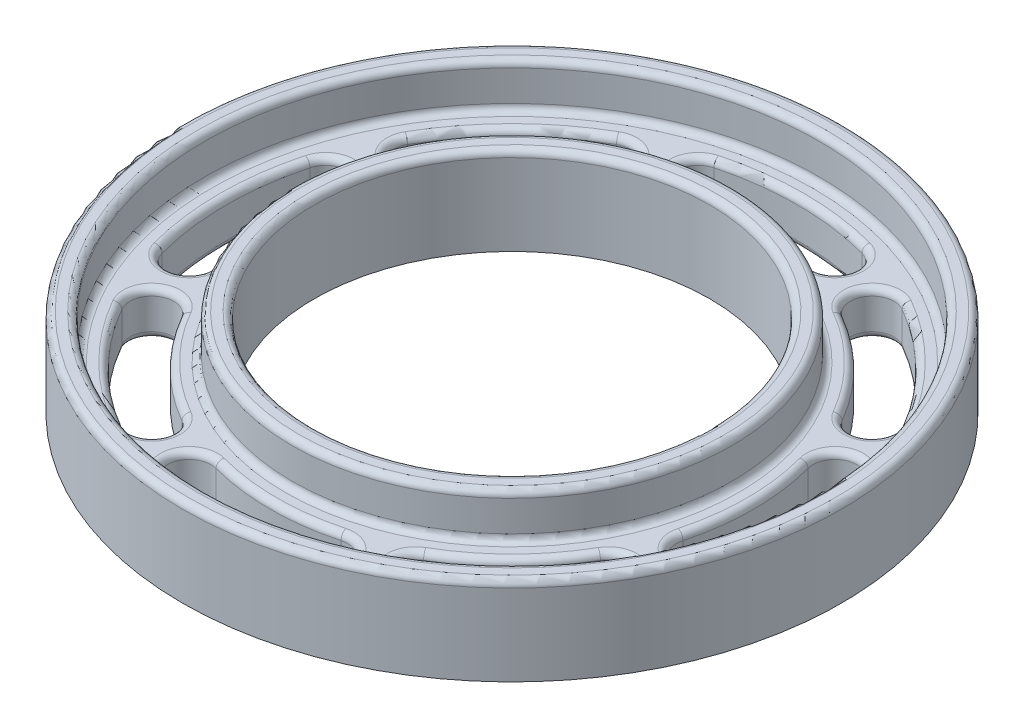
SolidWorks part; units mm, degrees
material "AISI 316 Stainless Steel Sheet (SS)"
ref_plane "Front Plane" through (0, 0, 0) normal (0, 0, 1) x (1, 0, 0)
ref_plane "Top Plane" through (0, 0, 0) normal (0, 1, 0) x (1, 0, 0)
ref_plane "Right Plane" through (0, 0, 0) normal (1, 0, 0) x (0, 0, -1)
sketch "Sketch1" plane through (0, 0, 0) normal (0, 1, 0) x (1, 0, 0)
  circle A0 centre (0, 0) radius 75
  circle A1 centre (0, 0) radius 45
  dimension "D1" = 150
  dimension "D2" = 90
extrude "Boss-Extrude1" add sketch "Sketch1" along normal blind 10
sketch "Sketch2" plane through (0, 10, 0) normal (0, 1, 0) x (1, 0, 0)
  circle A2 centre (0, 0) radius 70
  circle A3 centre (0, 0) radius 70
  circle A5 centre (0, 0) radius 50
  circle A6 centre (0, 0) radius 50
  circle M3 centre (0, 0) radius 75
  circle M4 centre (0, 0) radius 45
  dimension "D1" = 5
  dimension "D2" = 5
extrude "Boss-Extrude2" add sketch "Sketch2" along normal blind 10 contours A3 M3 | A6 M4
fillet "Fillet1" radius 1.5 6 edges at (0, 20, 45) (0, 20, 50) (0, 10, 70) (0, 10, 50) (0, 20, 75) (0, 20, 70)
sketch "Sketch3" plane through (0, 10, 0) normal (0, 1, 0) x (1, 0, 0)
  line L0 (0, 0) -> (0, 60) construction
  arc A0 (15.5291, 57.9555) -> (-15.5291, 57.9555) centre (0, 0) ccw construction
  arc A1 (16.8232, 62.7852) -> (-16.8232, 62.7852) centre (0, 0) ccw
  arc A2 (14.235, 53.1259) -> (-14.235, 53.1259) centre (0, 0) ccw
  arc A3 (14.235, 53.1259) -> (16.8232, 62.7852) centre (15.5291, 57.9555) ccw
  arc A4 (-16.8232, 62.7852) -> (-14.235, 53.1259) centre (-15.5291, 57.9555) ccw
  point P4 (0, 60)
  dimension "D1" = 10
  dimension "D3" = 60
  dimension "D2" = 30
extrude "Cut-Extrude1" cut sketch "Sketch3" against normal through all
fillet "Fillet2" radius 1.5 8 edges at (20.3588, 0, -56.6615) (0, 0, -55) (-20.3588, 0, -56.6615) (20.3588, 10, -56.6615) (0, 10, -55) (-20.3588, 10, -56.6615) (0, 0, -65) (0, 10, -65)
pattern_circular "CirPattern5" count 8 over 360 about axis through (0, 0, 0) along (0, 1, 0) of "Fillet2", "Cut-Extrude1"
